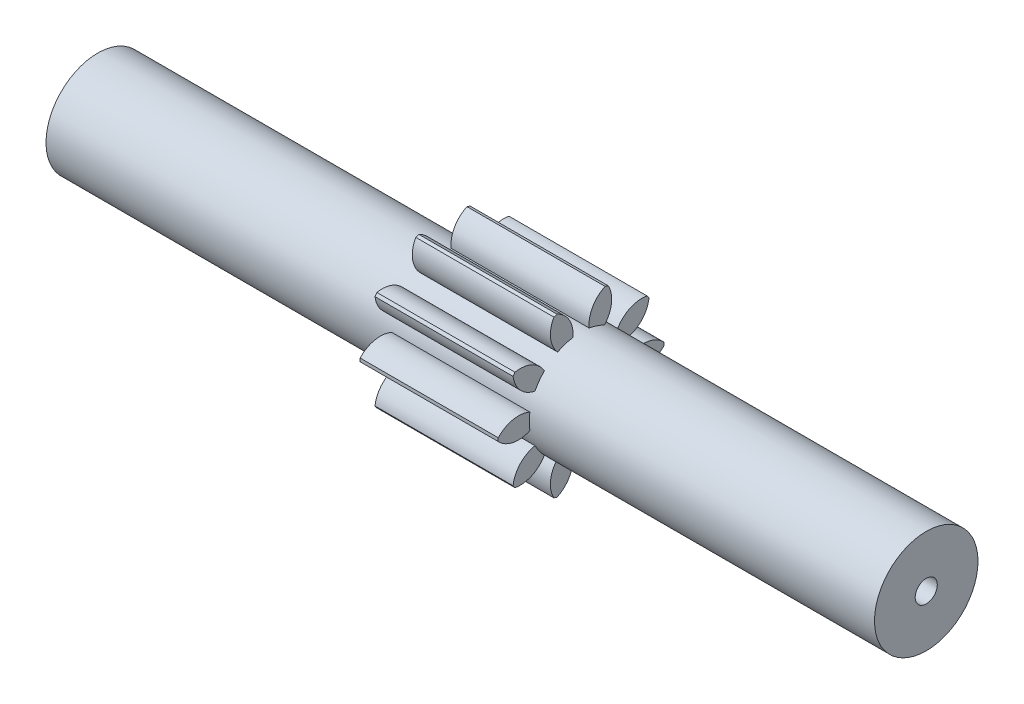
SolidWorks part; units mm, degrees
ref_plane "Plane1" through (0, 0, 0) normal (0, 0, 1) x (1, 0, 0)
ref_plane "Plane2" through (0, 0, 0) normal (0, 1, 0) x (1, 0, 0)
ref_plane "Plane3" through (0, 0, 0) normal (1, 0, 0) x (0, 0, -1)
other "Configuration Table"
sketch "HoldingSke" plane through (0, 0, 0) normal (0, 1, 0) x (1, 0, 0)
  line L0 (0, 0) -> (1.9696, -0.3473)
  line L1 (-15, 0) -> (100, 0) construction
  line L2 (0, 0) -> (-2.1039, 2.3779)
  line L3 (0, 0) -> (-11.863, 4.5341)
  line L4 (0, 0) -> (8.5048, 1.4996)
  line L5 (0, 0) -> (-28.1086, -10.4837)
  line L6 (0, 0) -> (-4.1448, -2.7965)
  line L7 (-2.1039, 2.3779) -> (4.3536, 31.6747)
  line L8 (-76.2, 54.61) -> (-76.1, 54.61)
  line L9 (-71.009, 38.7566) -> (-53.1078, 45.2721)
  line L10 (-76.2, 71.12) -> (104.1128, 71.12)
  line L11 (0, 0) -> (-5, 0)
  line L12 (-76.2, 101.6) -> (-76.181, 101.6)
  line L13 (24.9733, 27.94) -> (52.9518, 28.4284)
  line L14 (24.9733, 27.94) -> (24.9743, 27.94)
  line L15 (24.9733, 27.94) -> (100.4006, 29.5858)
  line L16 (-63.627, -0.5) -> (-12.827, -0.5)
  circle A0 centre (0, 0) radius 0.4
  circle A1 centre (0, 0) radius 1.874
  circle A2 centre (0, 0) radius 37.5
  circle A3 centre (0, 0) radius 0.4
  dimension "MHD" = 3.748
  dimension "Hub_dia" = 75
  dimension "Bore" = 0.8
  dimension "MBD" = 0.8
  dimension "Num_teeth" = 10
  dimension "Pitch" = 2
  dimension "Overall_len" = 30
  dimension "Show_teeth" = 10
  dimension "Thickness" = 5
  dimension "OAL" = 30.0001
  dimension "T_dim" = 0.1
  dimension "Ap" = 20
  dimension "H" = 19.05
  dimension "Pitch_radius" = 180.3128
  dimension "Width" = 5
  dimension "Backlash" = 0.019
  dimension "Addendum_fac" = 1
  dimension "Dedendum_fac" = 1.25
  dimension "Clearance_fac" = 0.25
  dimension "Dedendum_add" = 0.001
  dimension "Module" = 0.5
sketch "BasProSke" plane through (0, 0, 0) normal (0, 1, 0) x (1, 0, 0)
  line L0 (-10, 0) -> (60, 0) construction
  line L1 (0, 0) -> (0, 3)
  line L2 (0, 0) -> (5, 0)
  line L3 (5, 0) -> (5, 3)
  line L4 (5, 3) -> (0, 3)
  dimension "Thickness" = 5
  dimension "Diameter" = 6
revolve "Base-Revolve" add sketch "BasProSke" angle 360 about L0
sketch "TooCutSke" plane through (0, 0, 0) normal (1, 0, 0) x (0, 0, -1)
  line L1 (0, 0) -> (0, 107) construction
  line L2 (0, 0) -> (-0.4243, 2.4637) construction
  line L3 (0, 0) -> (-1.5292, 4.7063) construction
  line L4 (-0.4243, 2.4637) -> (-0.7646, 2.3532) construction
  arc A0 (0.2964, 1.8504) -> (-0.2964, 1.8504) centre (0, 0) ccw
  arc A1 (0.9059, 2.8866) -> (-0.9059, 2.8866) centre (0, 0) ccw
  circle A2 centre (0, 0) radius 2.5 construction
  circle A3 centre (0, 0) radius 2.3492 construction
  arc A4 (-0.2964, 1.8504) -> (-0.9059, 2.8866) centre (-1.2901, 1.9633) ccw
  arc A5 (0.9059, 2.8866) -> (0.2964, 1.8504) centre (1.2901, 1.9633) ccw
  dimension "Root_dia" = 3.748
  dimension "Overcut_dia" = 6.0508
  dimension "Pitch_dia" = 5
  dimension "Base_dia" = 4.6985
  dimension "Flank_rad" = 1
  dimension "Half_ang" = 18
  dimension "Half_CT" = 0.3578
extrude "ToothCut" cut sketch "TooCutSke" along normal through all
fillet "Breaks" [suppressed] radius 0.01
fillet "RootFillets" [suppressed] radius 0.126
pattern_circular "TeethCuts" count 10 every 36 about axis through (-10, 0, 0) along (1, 0, 0) of "ToothCut", "RootFillets", "Breaks"
sketch "HubNeaOneSke" plane through (0, 0, 0) normal (-1, 0, 0) x (0, 0, 1)
  circle A0 centre (0, 0) radius 1.874
  dimension "Diameter" = 3.748
extrude "HubNearOne" [suppressed] add sketch "HubNeaOneSke" along normal blind 25.0001
sketch "HubNeaBotSke" plane through (0, 0, 0) normal (-1, 0, 0) x (0, 0, 1)
  circle A0 centre (0, 0) radius 1.874
  dimension "Diameter" = 3.748
extrude "HubNearBoth" add sketch "HubNeaBotSke" along normal blind 12.5
ref_plane "FarPln" through (5, 0, 0) normal (1, 0, 0) x (0, 0, -1)
sketch "HubFarSke" plane through (5, 0, 0) normal (1, 0, 0) x (0, 0, -1)
  circle A0 centre (0, 0) radius 1.874
  dimension "Diameter" = 3.748
extrude "HubFar" add sketch "HubFarSke" along normal blind 12.5
sketch "BorSke" plane through (0, 0, 0) normal (1, 0, 0) x (0, 0, -1)
  circle A0 centre (0, 0) radius 0.4
  dimension "Diameter" = 0.8
extrude "Bore" cut sketch "BorSke" along normal mid plane 60.0001
sketch "KeySke" plane through (0, 0, 0) normal (1, 0, 0) x (0, 0, -1)
  line L0 (-0.05, 0) -> (-0.05, 0.5)
  line L1 (-0.05, 0.5) -> (0.05, 0.5)
  line L2 (0.05, 0.5) -> (0.05, 0)
  line L3 (0, 0) -> (0, 34) construction
  line L4 (-0.05, 0) -> (0.05, 0)
  dimension "Offset" = 0.5
  dimension "Width" = 0.1
extrude "Keyway" [suppressed] cut sketch "KeySke" along normal mid plane 60.0001
pattern_circular "Keyway2" [suppressed] count 2 every 90 about axis through (-10, 0, 0) along (1, 0, 0)
equation "' \"Module@HoldingSke\" = 6.35"
equation "' \"Num_teeth@HoldingSke\" = 12"
equation "' \"Ap@HoldingSke\" =  20"
equation "' \"Ap@HoldingSke\" = 20"
equation "' \"Width@HoldingSke\" = 0.5 * 25.4"
equation "' \"Hub_dia@HoldingSke\"= 1 * 25.4"
equation "' \"Hub_dia@HoldingSke\" = 1 * 25.4"
equation "' \"Overall_len@HoldingSke\" = 1.0 * 25.4"
equation "' \"Bore@HoldingSke\" = 0.75 * 25.4"
equation "' \"T_dim@HoldingSke\" = 0.1 * 25.4"
equation "' \"Width@KeySke\" = 0.25 * 25.4"
equation "' \"Show_teeth@HoldingSke\" = 13"
equation "' \"Backlash@HoldingSke\" = 0.009 * 25.4"
equation "' \"Addendum_fac@HoldingSke\" = 1.0"
equation "' \"Dedendum_fac@HoldingSke\" = 1.25"
equation "' \"Dedendum_add@HoldingSke\" = 0.00005 * 25.4"
equation "' \"Clearance_fac@HoldingSke\" = 0.25"
equation "\"Pitch@HoldingSke\" = 1 / \"Module@HoldingSke\""
equation "\"Overcut_dia@TooCutSke\" = (\"Num_teeth@HoldingSke\" + 2 * \"Addendum_fac@HoldingSke\") / \"Pitch@HoldingSke\" + 0.002 * 25.4"
equation "\"Pitch_dia@TooCutSke\" = \"Num_teeth@HoldingSke\" / \"Pitch@HoldingSke\""
equation "\"Base_dia@TooCutSke\" = \"Num_teeth@HoldingSke\" / \"Pitch@HoldingSke\" * cos((\"Ap@HoldingSke\"  * 3.14159265 / 180))"
equation "\"Root_dia@TooCutSke\" = (\"Num_teeth@HoldingSke\" + 2) / \"Pitch@HoldingSke\" - 2 * (\"Addendum_fac@HoldingSke\" + \"Dedendum_fac@HoldingSke\") / \"Pitch@HoldingSke\" - \"Dedendum_add@HoldingSke\" * 2"
equation "\"Half_ang@TooCutSke\" = 180 / \"Num_teeth@HoldingSke\""
equation "\"Half_CT@TooCutSke\" = \"Num_teeth@HoldingSke\" / \"Pitch@HoldingSke\" * sin((3.14159265 / 2 / \"Num_teeth@HoldingSke\")) / 2 - 7 * \"Backlash@HoldingSke\" / 4"
equation "\"Flank_rad@TooCutSke\" = \"Num_teeth@HoldingSke\" / \"Pitch@HoldingSke\" / 5"
equation "\"Radius@RootFillets\" = \"Clearance_fac@HoldingSke\" / \"Pitch@HoldingSke\" + \"Dedendum_add@HoldingSke\""
equation "\"Break_rad@Breaks\" = 0.02 / \"Pitch@HoldingSke\""
equation "\"Thickness@HoldingSke\" = \"Width@HoldingSke\""
equation "\"OAL@HoldingSke\" = \"Thickness@HoldingSke\""
equation "\"MHD@HoldingSke\" = (\"Num_teeth@HoldingSke\" + 2) / \"Pitch@HoldingSke\" - 2 * (\"Addendum_fac@HoldingSke\" + \"Dedendum_fac@HoldingSke\")  / \"Pitch@HoldingSke\" - \"Dedendum_add@HoldingSke\" * 2"
equation "\"MBD@HoldingSke\" = (\"Num_teeth@HoldingSke\" + 2) / \"Pitch@HoldingSke\" - 2 * (\"Addendum_fac@HoldingSke\" + \"Dedendum_fac@HoldingSke\")  / \"Pitch@HoldingSke\" - \"Dedendum_add@HoldingSke\" * 2 - 0.002 * 25.4"
equation "\"MHD@HoldingSke\" = ((sgn( \"MHD@HoldingSke\" - \"Hub_dia@HoldingSke\" )-1)*( \"MHD@HoldingSke\" - \"Hub_dia@HoldingSke\" ))/-2+ \"Hub_dia@HoldingSke\""
equation "\"MBD@HoldingSke\" = ((sgn( \"MBD@HoldingSke\" - \"Bore@HoldingSke\" )-1)*( \"MBD@HoldingSke\" - \"Bore@HoldingSke\" ))/-2+ \"Bore@HoldingSke\""
equation "\"OAL@HoldingSke\" = ((sgn( \"OAL@HoldingSke\" - \"Overall_len@HoldingSke\" )+1)*( \"OAL@HoldingSke\" - \"Overall_len@HoldingSke\" ))/2 + \"Overall_len@HoldingSke\" + 0.000002 * 25.4"
equation "\"Num_teeth@TeethCuts\" = int( \"Show_teeth@HoldingSke\" ) + 1"
equation "\"Num_teeth@TeethCuts\" = ((sgn( \"Num_teeth@TeethCuts\" - \"Num_teeth@HoldingSke\" )-1)*( \"Num_teeth@TeethCuts\" - \"Num_teeth@HoldingSke\" ))/-2+ \"Num_teeth@HoldingSke\""
equation "\"Num_teeth@TeethCuts\" = ((sgn( \"Num_teeth@TeethCuts\" - 2.0)+1)*( \"Num_teeth@TeethCuts\" - 2.0))/2 +2.0"
equation "\"Angle@TeethCuts\" = 360.0 / \"Num_teeth@HoldingSke\""
equation "\"Diameter@BasProSke\" = (\"Num_teeth@HoldingSke\" + 2 * \"Addendum_fac@HoldingSke\") / \"Pitch@HoldingSke\""
equation "\"Thickness@BasProSke\"  = \"Thickness@HoldingSke\""
equation "' \"Fillet_rad@BasProSke\" =  \"Thickness@HoldingSke\" * 0.05"
equation "' \"Fillet_rad@BasProSke\" = \"Thickness@HoldingSke\" * 0.05"
equation "\"MHD@HoldingSke\" = ((sgn( \"MHD@HoldingSke\" - \"Root_dia@TooCutSke\" )-1)*( \"MHD@HoldingSke\" - \"Root_dia@TooCutSke\" ))/-2+ \"Root_dia@TooCutSke\""
equation "\"Diameter@HubNeaOneSke\" = \"MHD@HoldingSke\""
equation "\"Length@HubNearOne\" = \"OAL@HoldingSke\" - \"Thickness@BasProSke\""
equation "\"Diameter@HubNeaBotSke\" = \"MHD@HoldingSke\""
equation "\"Length@HubNearBoth\" = ( \"OAL@HoldingSke\" - \"Thickness@BasProSke\" ) / 2.0"
equation "\"Thickness@FarPln\" = \"Thickness@BasProSke\""
equation "\"Diameter@HubFarSke\" = \"MHD@HoldingSke\""
equation "\"Length@HubFar\" = ( \"OAL@HoldingSke\" - \"Thickness@BasProSke\" ) / 2.0"
equation "\"Diameter@BorSke\" = \"MBD@HoldingSke\""
equation "\"D1@Bore\" = \"OAL@HoldingSke\" * 2.0"
equation "\"D1@Keyway\" = \"OAL@HoldingSke\" * 2.0"
equation "\"Offset@KeySke\" = \"T_dim@HoldingSke\" + \"MBD@HoldingSke\" / 2.0"
